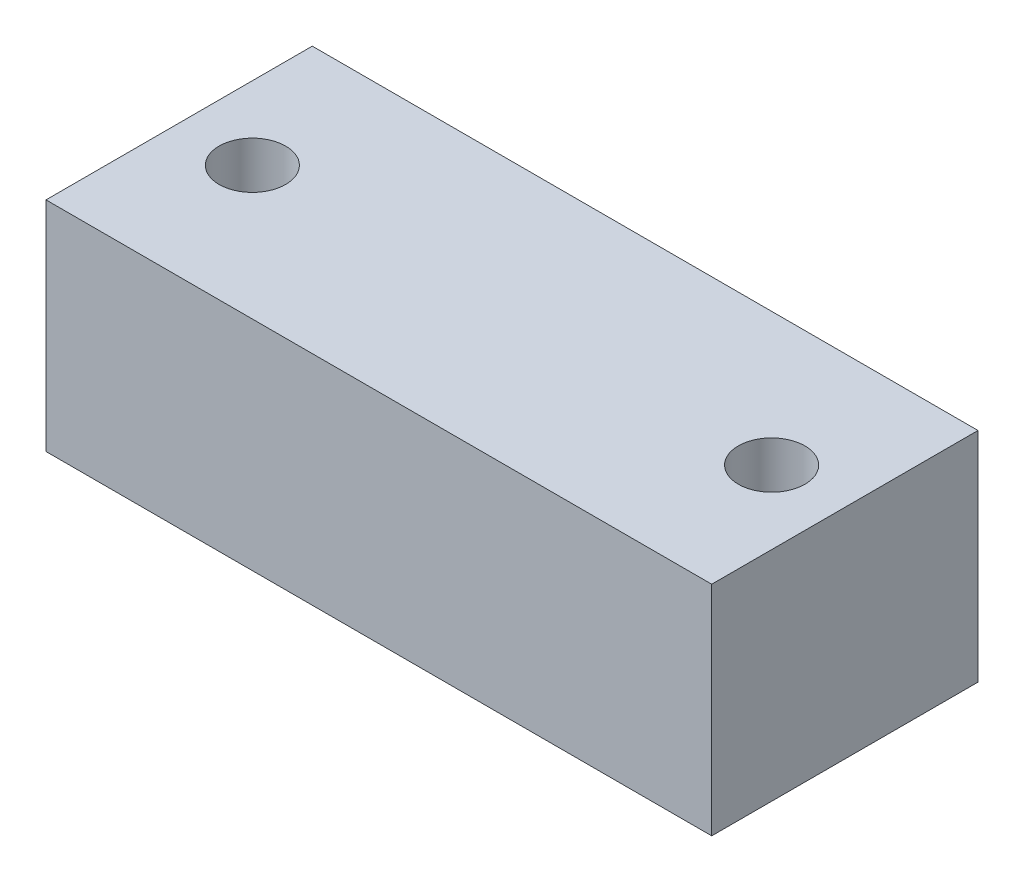
SolidWorks part; units mm, degrees
material "Polyurethane Foam Flexible"
ref_plane "Front Plane" through (0, 0, 0) normal (0, 0, 1) x (1, 0, 0)
ref_plane "Top Plane" through (0, 0, 0) normal (0, 1, 0) x (1, 0, 0)
ref_plane "Right Plane" through (0, 0, 0) normal (1, 0, 0) x (0, 0, -1)
sketch "Sketch1" plane through (0, 0, 0) normal (0, 1, 0) x (1, 0, 0)
  line L0 (0, 39.9043) -> (0, -42.1336) construction
  line L1 (-25, 10) -> (25, 10)
  line L2 (-25, 10) -> (-25, -10)
  line L3 (-25, -10) -> (25, -10)
  line L4 (25, 10) -> (25, -10)
  line L5 (-44.6654, 0) -> (93.1046, 0) construction
  dimension "D1" = 50
  dimension "D2" = 20
extrude "Boss-Extrude1" add sketch "Sketch1" along normal blind 16.37
sketch "Sketch3" plane through (0, 16.37, 0) normal (0, 1, 0) x (1, 0, 0)
  circle A1 centre (19.5, 0) radius 2.5
  circle A2 centre (19.5, 0) radius 2.5
  circle A3 centre (-19.5, 0) radius 2.5
  circle A4 centre (-19.5, 0) radius 2.5
  dimension "D1" = 0
  dimension "D2" = 0
extrude "Cut-Extrude2" cut sketch "Sketch3" against normal through all
